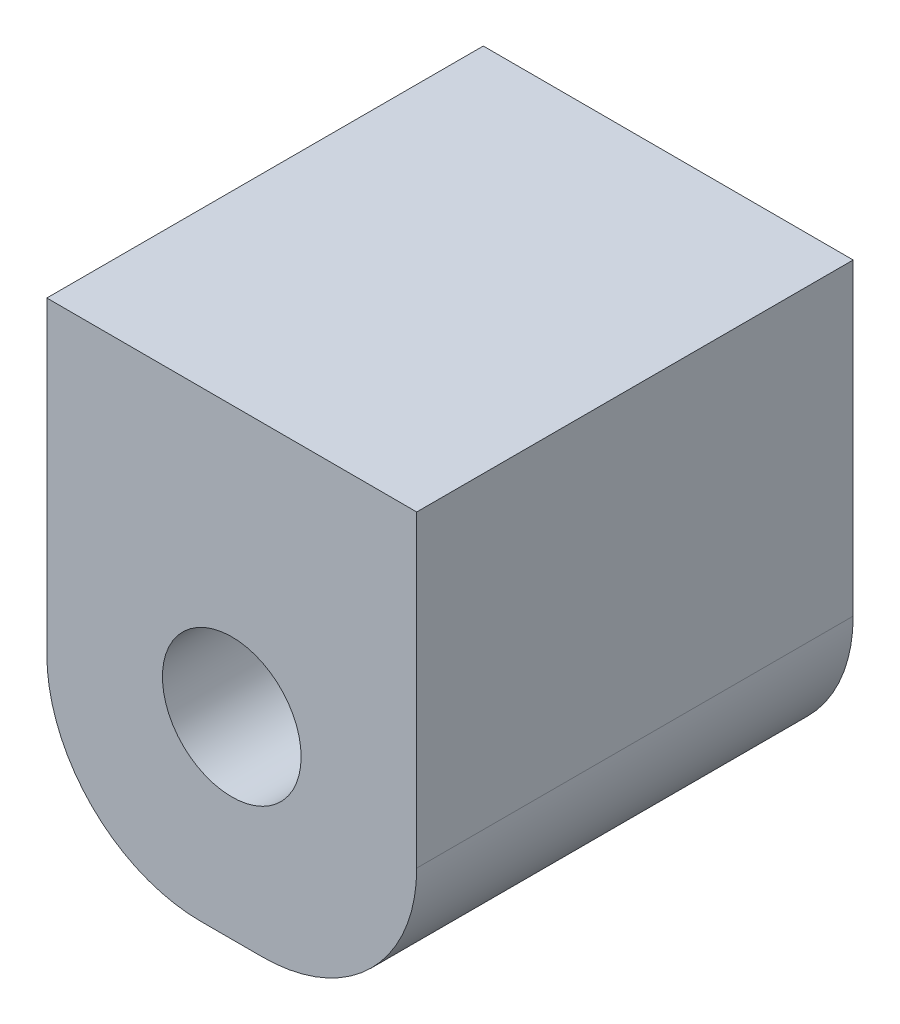
SolidWorks part; units mm, degrees
ref_plane "Alzado" through (0, 0, 0) normal (0, 0, 1) x (1, 0, 0)
ref_plane "Planta" through (0, 0, 0) normal (0, 1, 0) x (1, 0, 0)
ref_plane "Vista lateral" through (0, 0, 0) normal (1, 0, 0) x (0, 0, -1)
sketch "Croquis1" plane through (0, 0, 0) normal (0, 0, 1) x (1, 0, 0)
  line L0 (14.5278, -0.0086) -> (38.5278, -0.0328)
  line L3 (38.5278, -5.0449) -> (38.5278, -30.0449)
  line L4 (38.5278, -30.0449) -> (14.5278, -30.0449)
  line L5 (14.5278, -30.0449) -> (14.5278, -5.0449)
  line L8 (14.5278, -5.0449) -> (14.5278, -0.0086)
  line L9 (38.5278, -5.0449) -> (38.5278, -0.0328)
  circle A0 centre (26.5278, -17.5449) radius 4.5
  dimension "D5" = 9
  dimension "D3" = 12.5
  dimension "D4" = 25
  dimension "D7" = 24
  dimension "D8" = 12
  dimension "D9" = 12
extrude "Saliente-Extruir1" add sketch "Croquis1" along normal blind 28.32
fillet "Redondeo1" radius 10 2 edges at (14.5278, -30.0449, 14.16) (38.5278, -30.0449, 14.16)
